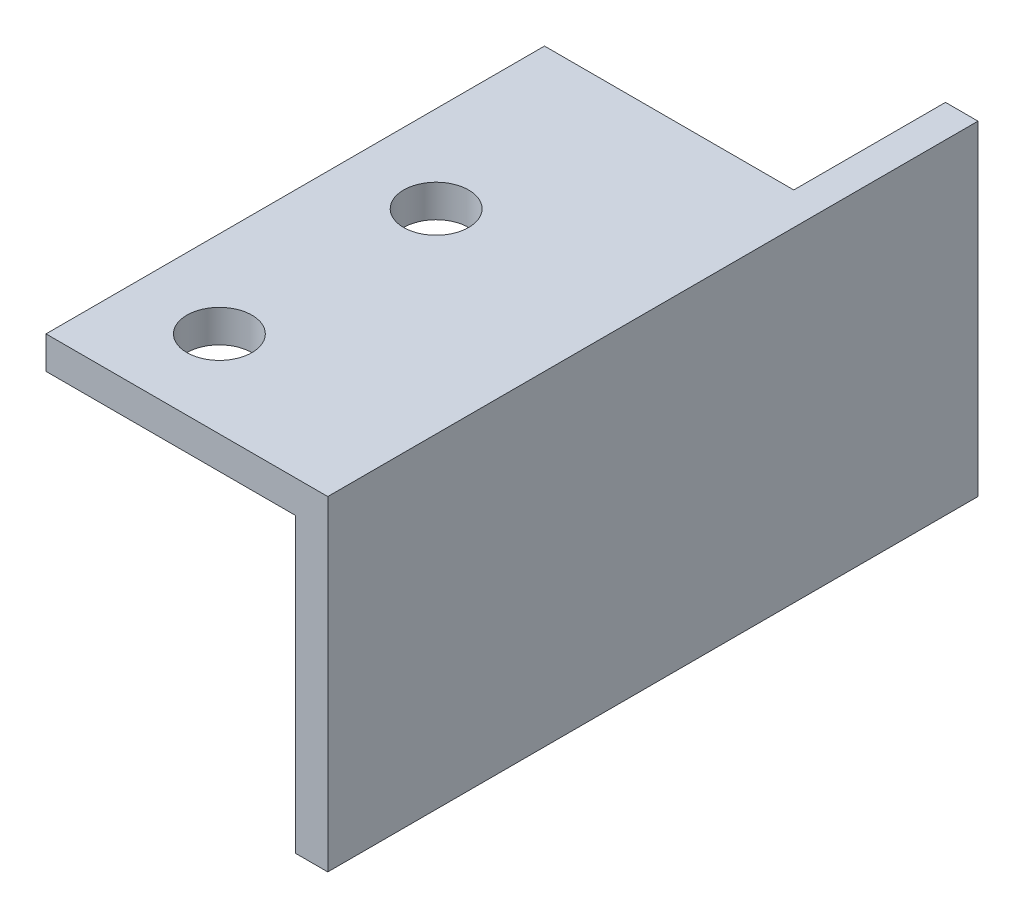
SolidWorks part; units mm, degrees
ref_plane "Plan de face" through (0, 0, 0) normal (0, 0, 1) x (1, 0, 0)
ref_plane "Plan de dessus" through (0, 0, 0) normal (0, 1, 0) x (1, 0, 0)
ref_plane "Plan de droite" through (0, 0, 0) normal (1, 0, 0) x (0, 0, -1)
sketch "Esquisse1" plane through (0, 0, 0) normal (0, 0, 1) x (1, 0, 0)
  line L0 (-276.4656, 896.942) -> (-276.4656, 911.942)
  line L1 (-276.4656, 911.942) -> (-289.4656, 911.942)
  line L2 (-289.4656, 911.942) -> (-289.4656, 910.442)
  line L3 (-289.4656, 910.442) -> (-277.9656, 910.442)
  line L4 (-277.9656, 910.442) -> (-277.9656, 896.942)
  line L5 (-277.9656, 896.942) -> (-276.4656, 896.942)
  dimension "D1" = 1.5
  dimension "D2" = 1.5
  dimension "D3" = 13
  dimension "D4" = 15
extrude "Extrusion1" add sketch "Esquisse1" along normal blind 30
sketch "Esquisse2" plane through (0, 911.942, 0) normal (0, 1, 0) x (-1, 0, 0)
  line L0 (276.4656, 30) -> (289.4656, 30) construction
  line L1 (289.4656, 30) -> (289.4656, 0) construction
  line L2 (276.4656, 30) -> (276.4656, 0) construction
  line L3 (289.4656, 0) -> (277.9656, 0)
  line L4 (289.4656, 0) -> (289.4656, 7)
  line L5 (289.4656, 7) -> (277.9656, 7)
  line L6 (277.9656, 0) -> (277.9656, 7)
  circle A0 centre (285.4656, 16) radius 1.5
  circle A1 centre (285.4656, 26) radius 1.5
  dimension "D1" = 4
  dimension "D2" = 10
  dimension "D3" = 4
  dimension "D4" = 4
  dimension "D5" = 1.5
  dimension "D6" = 7
extrude "Extrusion2" cut sketch "Esquisse2" against normal blind 30
